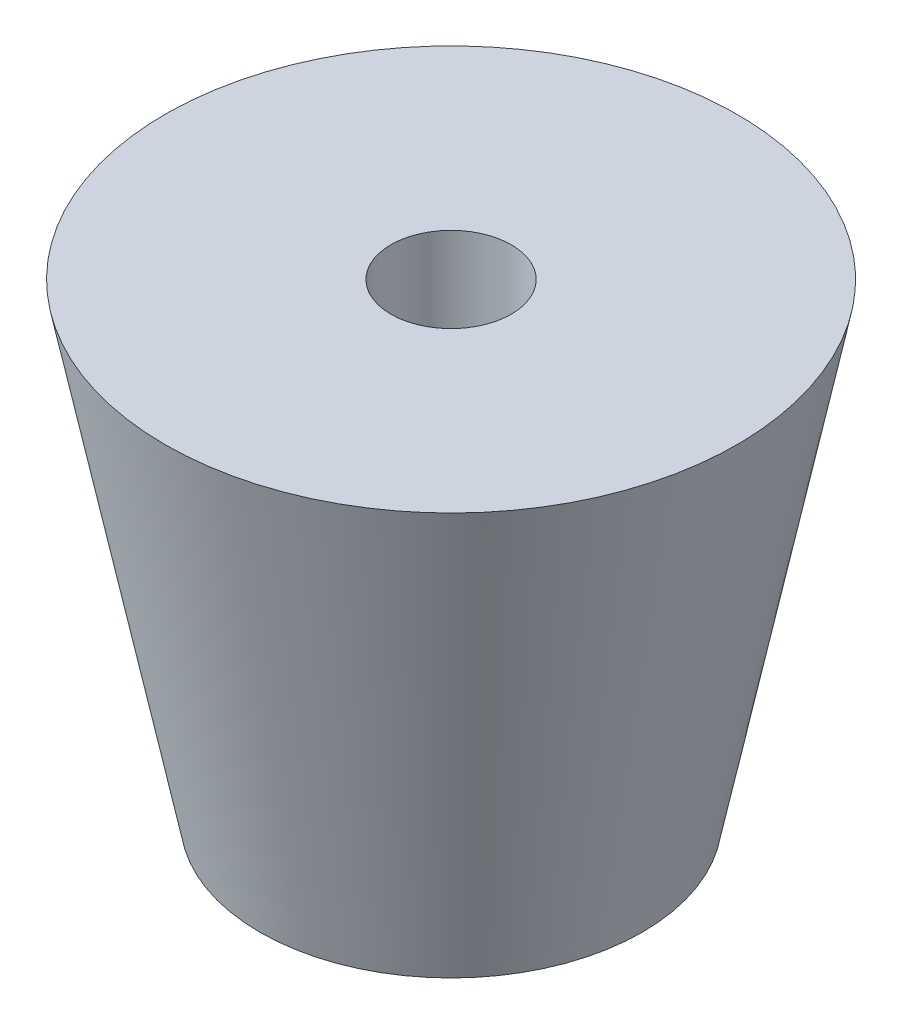
SolidWorks part; units mm, degrees
material "Guma"
ref_plane "Přední rovina" through (0, 0, 0) normal (0, 0, 1) x (1, 0, 0)
ref_plane "Horní rovina" through (0, 0, 0) normal (0, 1, 0) x (1, 0, 0)
ref_plane "Pravá rovina" through (0, 0, 0) normal (1, 0, 0) x (0, 0, -1)
sketch "Skica1" plane through (0, 0, 0) normal (0, 0, 1) x (1, 0, 0)
  line L0 (0, 11.6167) -> (0, -11.6872) construction
  line L1 (2, 7.3679) -> (9.5, 7.3679)
  line L2 (9.5, 7.3679) -> (6.35, -8.2321)
  line L3 (2, -3.4321) -> (3.95, -3.4321)
  line L4 (3.95, -3.4321) -> (3.95, -8.2321)
  line L5 (3.95, -8.2321) -> (6.35, -8.2321)
  line L6 (2, -3.4321) -> (2, 7.3679)
  dimension "D1" = 2
  dimension "D2" = 9.5
  dimension "D3" = 6.35
  dimension "D4" = 15.6
  dimension "D5" = 3.95
  dimension "D6" = 2
  dimension "D7" = 4.8
revolve "Rotovat1" add sketch "Skica1" angle 360 about L0
